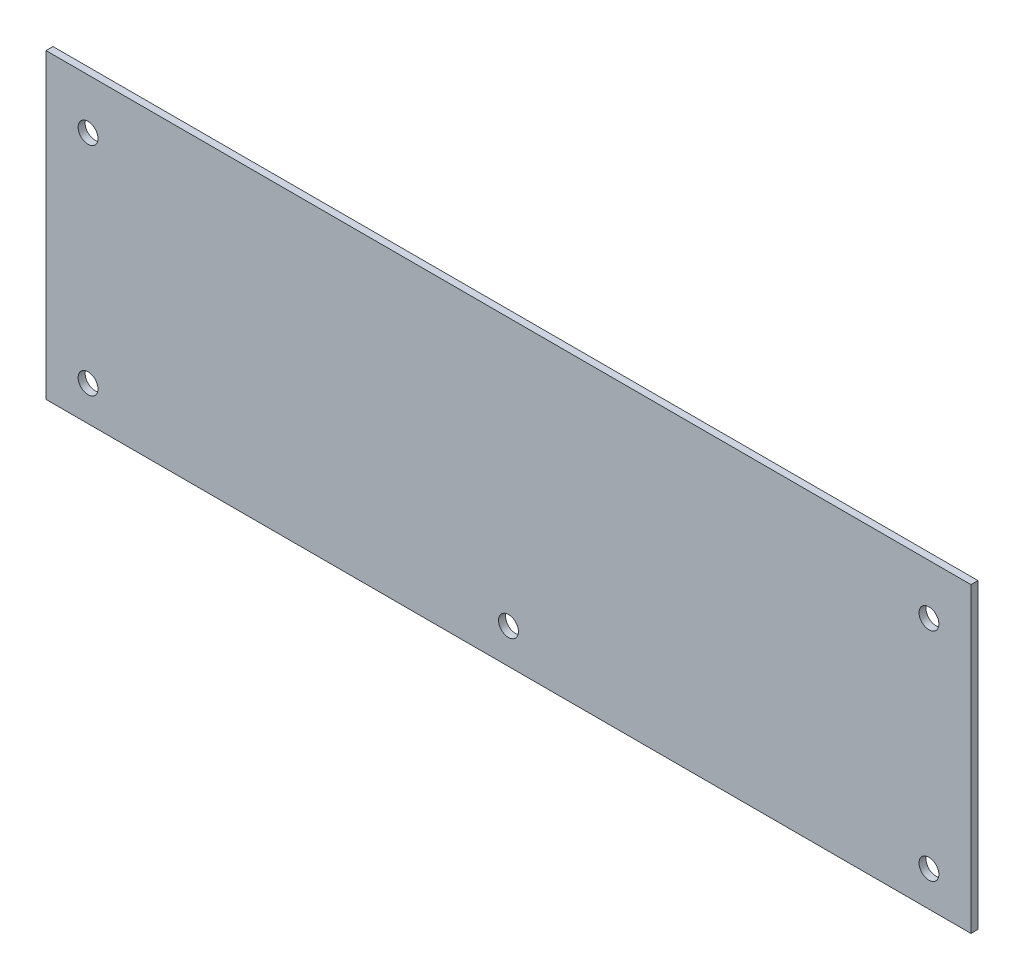
SolidWorks part; units mm, degrees
ref_plane "Front Plane" through (0, 0, 0) normal (0, 0, 1) x (1, 0, 0)
ref_plane "Top Plane" through (0, 0, 0) normal (0, 1, 0) x (1, 0, 0)
ref_plane "Right Plane" through (0, 0, 0) normal (1, 0, 0) x (0, 0, -1)
sketch "Sketch1" plane through (0, 0, 0) normal (0, 0, 1) x (1, 0, 0)
  line L1 (0, 0) -> (402.7, 0)
  line L2 (0, 0) -> (0, 86.34)
  line L3 (29, 129.34) -> (373.7, 129.34)
  line L4 (402.7, 0) -> (402.7, 86.34)
  line L7 (0, 86.34) -> (29, 86.34)
  line L8 (29, 129.34) -> (29, 86.34)
  line L10 (373.7, 129.34) -> (373.7, 86.34)
  line L11 (373.7, 86.34) -> (402.7, 86.34)
  circle A0 centre (21.35, 71.34) radius 4
  circle A1 centre (21.35, 15) radius 4
  circle A2 centre (381.35, 15) radius 4
  circle A3 centre (381.35, 71.34) radius 4
  circle A4 centre (199, 15) radius 4
  dimension "D3" = 8
  dimension "D1" = 402.7
  dimension "D2" = 129.34
  dimension "D4" = 21.35
  dimension "D5" = 15
  dimension "D6" = 21.35
  dimension "D7" = 15
  dimension "D8" = 15
  dimension "D9" = 199
  dimension "D10" = 43
  dimension "D11" = 29
  dimension "D12" = 29
extrude "Boss-Extrude1" add sketch "Sketch1" along normal blind 3
sketch "Croquis1" plane through (0, 0, 3) normal (0, 0, 1) x (1, 0, 0)
  line L1 (29, 86.34) -> (0, 86.34)
  line L2 (29, 86.34) -> (29, 129.34)
  line L3 (29, 129.34) -> (0, 129.34)
  line L4 (0, 86.34) -> (0, 129.34)
  line L5 (373.7, 86.34) -> (402.7, 86.34)
  line L6 (373.7, 86.34) -> (373.7, 129.34)
  line L7 (373.7, 129.34) -> (402.7, 129.34)
  line L8 (402.7, 86.34) -> (402.7, 129.34)
extrude "Saliente-Extruir1" add sketch "Croquis1" against normal blind 3
sketch "Croquis2" plane through (0, 0, 3) normal (0, 0, 1) x (1, 0, 0)
  line L0 (402.7, 129.34) -> (0, 129.34) construction
  line L1 (0, 129.34) -> (0, 0) construction
  line L2 (402.7, 0) -> (402.7, 129.34) construction
  circle A0 centre (15, 107.84) radius 4.25
  circle A1 centre (387.7, 107.84) radius 4.25
  dimension "D1" = 21.5
  dimension "D3" = 15
  dimension "D2" = 15
extrude "Cortar-Extruir1" cut sketch "Croquis2" against normal blind 3
sketch "Croquis4" plane through (0, 0, 3) normal (0, 0, 1) x (1, 0, 0)
  line L0 (402.7, 129.34) -> (0, 129.34) construction
  line L1 (0, 0) -> (3.35, 0)
  line L2 (0, 0) -> (0, 129.34)
  line L3 (0, 129.34) -> (3.35, 129.34)
  line L4 (3.35, 0) -> (3.35, 129.34)
  line L5 (0, 0) -> (402.7, 0) construction
  line L6 (402.7, 0) -> (399.35, 0)
  line L7 (402.7, 0) -> (402.7, 129.34)
  line L8 (402.7, 129.34) -> (399.35, 129.34)
  line L9 (399.35, 0) -> (399.35, 129.34)
  point P14 (201.35, 0)
  dimension "D1" = 396
  dimension "D2" = 198
extrude "Cortar-Extruir2" cut sketch "Croquis4" against normal blind 3
sketch "Croquis5" plane through (0, 0, 3) normal (0, 0, 1) x (1, 0, 0)
  circle A0 centre (199, 15) radius 4.5
  circle A1 centre (21.35, 15) radius 4.5
  circle A2 centre (21.35, 71.34) radius 4.5
  circle A3 centre (15, 107.84) radius 4.5
  circle A4 centre (387.7, 107.84) radius 4.5
  circle A5 centre (381.35, 71.34) radius 4.5
  circle A6 centre (381.35, 15) radius 4.5
extrude "Saliente-Extruir2" add sketch "Croquis5" against normal blind 3
sketch "Croquis6" plane through (0, 0, 3) normal (0, 0, 1) x (1, 0, 0)
  line L0 (3.35, 0) -> (399.35, 0) construction
  line L1 (399.35, 129.34) -> (3.35, 129.34) construction
  line L2 (3.35, 0) -> (3.35, 129.34) construction
  line L3 (399.35, 129.34) -> (399.35, 0) construction
  circle A0 centre (21.35, 107.84) radius 4.25
  circle A1 centre (21.35, 15) radius 4.25
  circle A2 centre (201.35, 15) radius 4.25
  circle A3 centre (381.35, 15) radius 4.25
  circle A4 centre (381.35, 107.84) radius 4.25
  dimension "D1" = 15
  dimension "D5" = 18
  dimension "D2" = 21.5
  dimension "D3" = 18
  dimension "D4" = 18
extrude "Cortar-Extruir3" cut sketch "Croquis6" against normal blind 3
